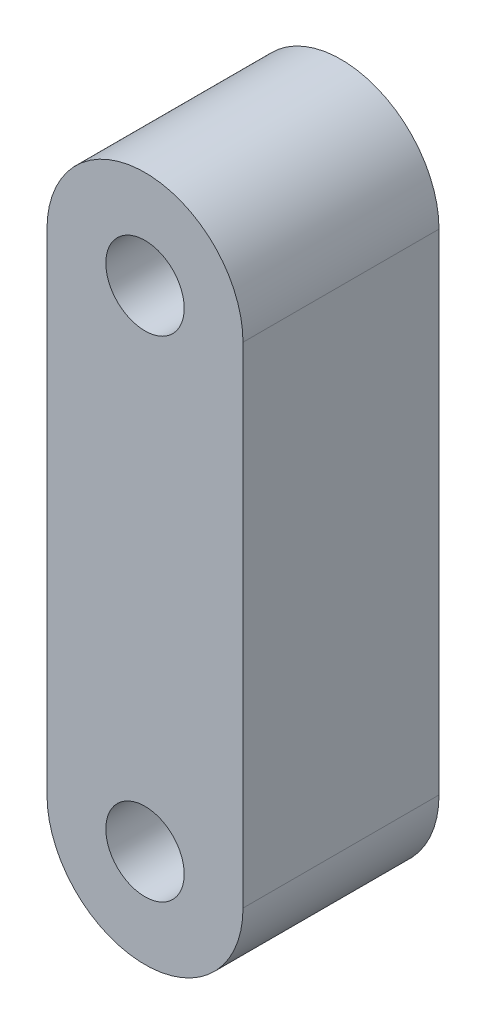
SolidWorks part; units mm, degrees
ref_plane "Plan de face" through (0, 0, 0) normal (0, 0, 1) x (1, 0, 0)
ref_plane "Plan de dessus" through (0, 0, 0) normal (0, 1, 0) x (1, 0, 0)
ref_plane "Plan de droite" through (0, 0, 0) normal (1, 0, 0) x (0, 0, -1)
sketch "Esquisse1" plane through (0, 0, 0) normal (0, 0, 1) x (1, 0, 0)
  line L0 (0, 0) -> (0, 50) construction
  line L1 (-10, 0) -> (-10, 50)
  line L2 (10, 0) -> (10, 50)
  arc A0 (-10, 0) -> (10, 0) centre (0, 0) ccw
  arc A1 (10, 50) -> (-10, 50) centre (0, 50) ccw
  circle A2 centre (0, 50) radius 4
  circle A3 centre (0, 0) radius 4
  point P3 (0, 25)
  point P12 (0, 0)
  dimension "D2" = 10
  dimension "D3" = 8
  dimension "D1" = 50
extrude "Boss.-Extru.1" add sketch "Esquisse1" along normal blind 20
